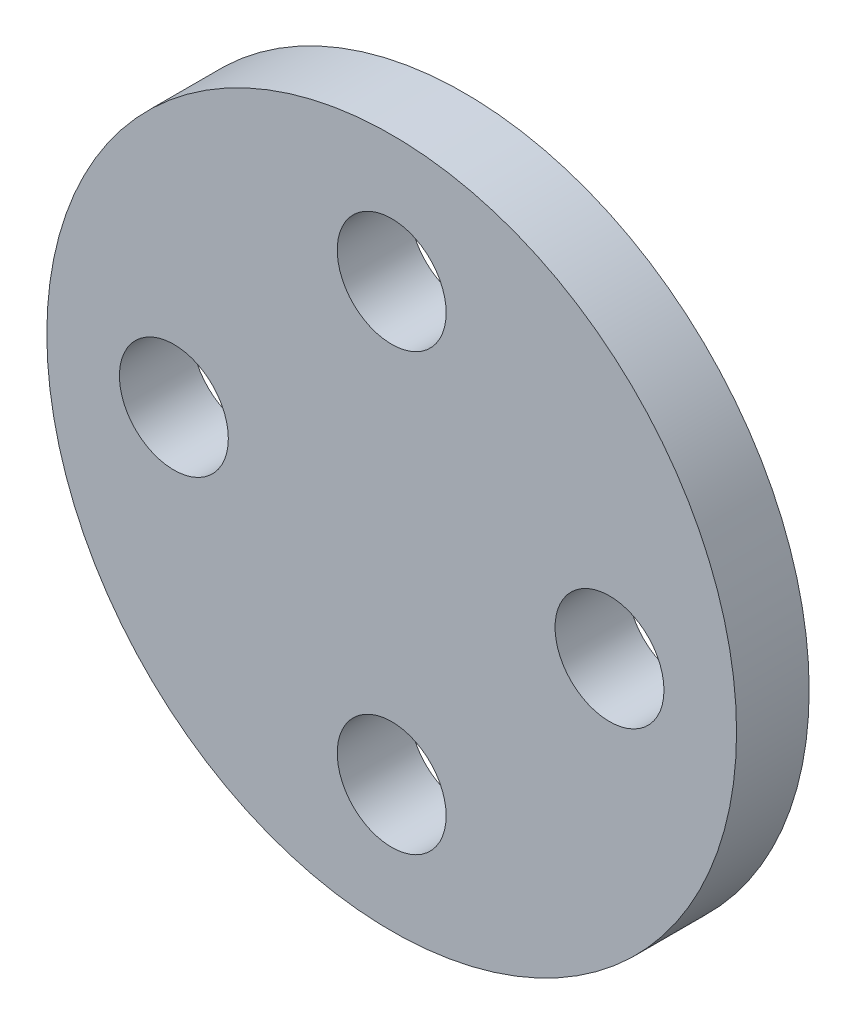
SolidWorks part; units mm, degrees
ref_plane "Front Plane" through (0, 0, 0) normal (0, 0, 1) x (1, 0, 0)
ref_plane "Top Plane" through (0, 0, 0) normal (0, 1, 0) x (1, 0, 0)
ref_plane "Right Plane" through (0, 0, 0) normal (1, 0, 0) x (0, 0, -1)
sketch "Sketch1" plane through (0, 0, 0) normal (0, 0, 1) x (1, 0, 0)
  circle A0 centre (0, 0) radius 15.0812
  circle A1 centre (0, 9.525) radius 2.3812
  circle A2 centre (9.525, 0) radius 2.3813
  circle A3 centre (0, -9.525) radius 2.3813
  circle A4 centre (-9.525, 0) radius 2.3813
  point P14 (0, 0)
  dimension "D1" = 30.1625
  dimension "D2" = 4.7625
  dimension "D3" = 9.525
  dimension "D4" = 4
extrude "Boss-Extrude1" add sketch "Sketch1" along normal blind 3.175
